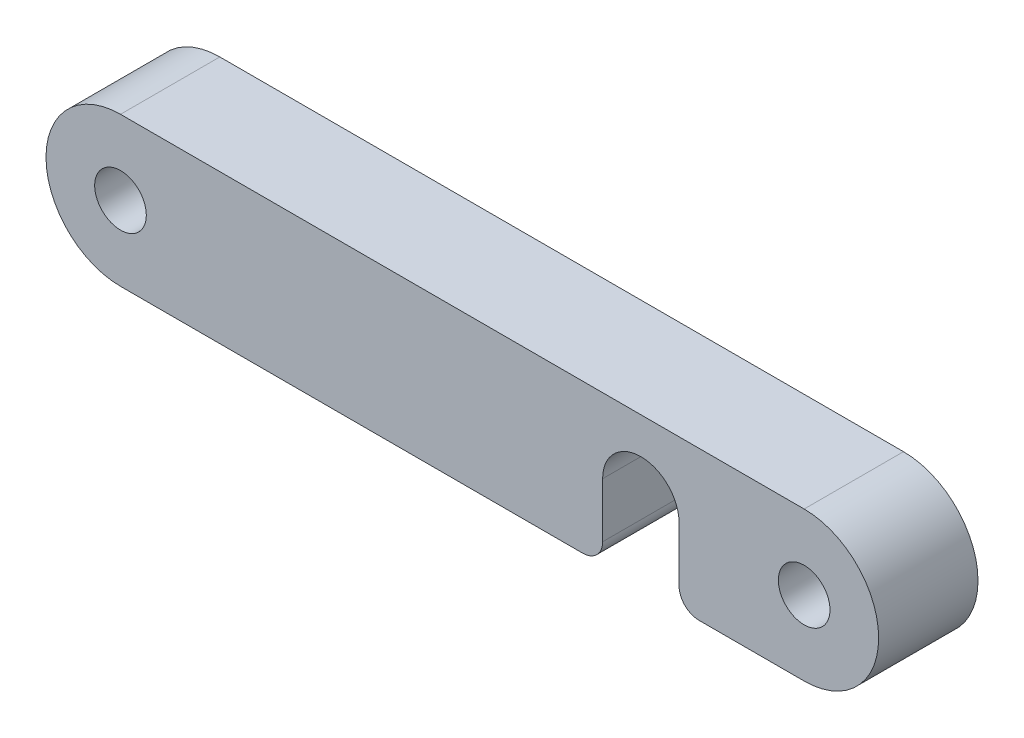
SolidWorks part; units mm, degrees
ref_plane "Front Plane" through (0, 0, 0) normal (0, 0, 1) x (1, 0, 0)
ref_plane "Top Plane" through (0, 0, 0) normal (0, 1, 0) x (1, 0, 0)
ref_plane "Right Plane" through (0, 0, 0) normal (1, 0, 0) x (0, 0, -1)
sketch "Sketch1" plane through (0, 0, 0) normal (0, 0, 1) x (1, 0, 0)
  line L0 (-21.8515, 0) -> (21.8515, 0) construction
  line L1 (-21.8515, 4.7625) -> (21.8515, 4.7625)
  line L2 (-21.8515, -4.7625) -> (21.8515, -4.7625)
  arc A0 (-21.8515, 4.7625) -> (-21.8515, -4.7625) centre (-21.8515, 0) ccw
  arc A1 (21.8515, -4.7625) -> (21.8515, 4.7625) centre (21.8515, 0) ccw
  circle A2 centre (21.8515, 0) radius 1.65
  circle A3 centre (-21.8515, 0) radius 1.65
  point P2 (0, 0)
  dimension "D1" = 53.228
  dimension "D2" = 3.3
  dimension "D3" = 9.525
extrude "Boss-Extrude1" add sketch "Sketch1" along normal blind 6.35
sketch "Sketch2" plane through (0, 0, 0) normal (0, 0, -1) x (-1, 0, 0)
  circle A0 centre (21.8515, 0) radius 3.1
  dimension "D1" = 6.2
extrude "Cut-Extrude1" [suppressed] cut sketch "Sketch2" against normal blind 3.75
sketch "Sketch4" plane through (0, 0, 0) normal (0, 0, -1) x (-1, 0, 0)
  line L2 (-8.9695, 0) -> (-8.9695, -3.4925)
  line L3 (-13.857, -3.4925) -> (-13.857, 0)
  line L4 (-15.127, -4.7625) -> (-7.6995, -4.7625)
  arc A3 (-8.9695, -3.4925) -> (-7.6995, -4.7625) centre (-7.6995, -3.4925) ccw
  arc A4 (-8.9695, 0) -> (-13.857, 0) centre (-11.4132, 0) ccw
  arc A5 (-15.127, -4.7625) -> (-13.857, -3.4925) centre (-15.127, -3.4925) ccw
extrude "Cut-Extrude3" cut sketch "Sketch4" against normal through all
